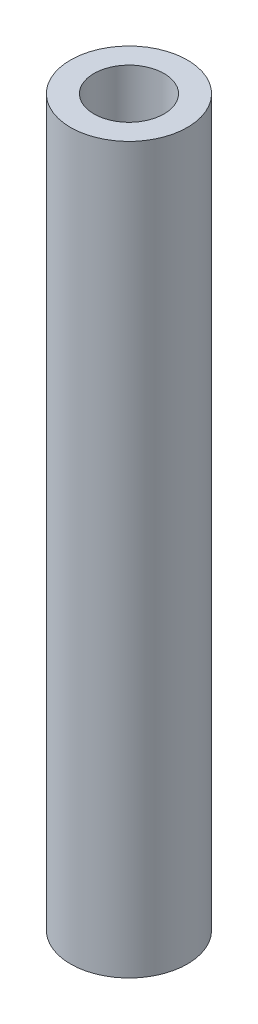
SolidWorks part; units mm, degrees
ref_plane "Front Plane" through (0, 0, 0) normal (0, 0, 1) x (1, 0, 0)
ref_plane "Top Plane" through (0, 0, 0) normal (0, 1, 0) x (1, 0, 0)
ref_plane "Right Plane" through (0, 0, 0) normal (1, 0, 0) x (0, 0, -1)
sketch "Sketch1" plane through (0, 0, 0) normal (0, 1, 0) x (1, 0, 0)
  circle A0 centre (0, 0) radius 5
  circle A1 centre (0, 0) radius 3
  dimension "D1" = 2
extrude "Boss-Extrude1" add sketch "Sketch1" along normal blind 62
